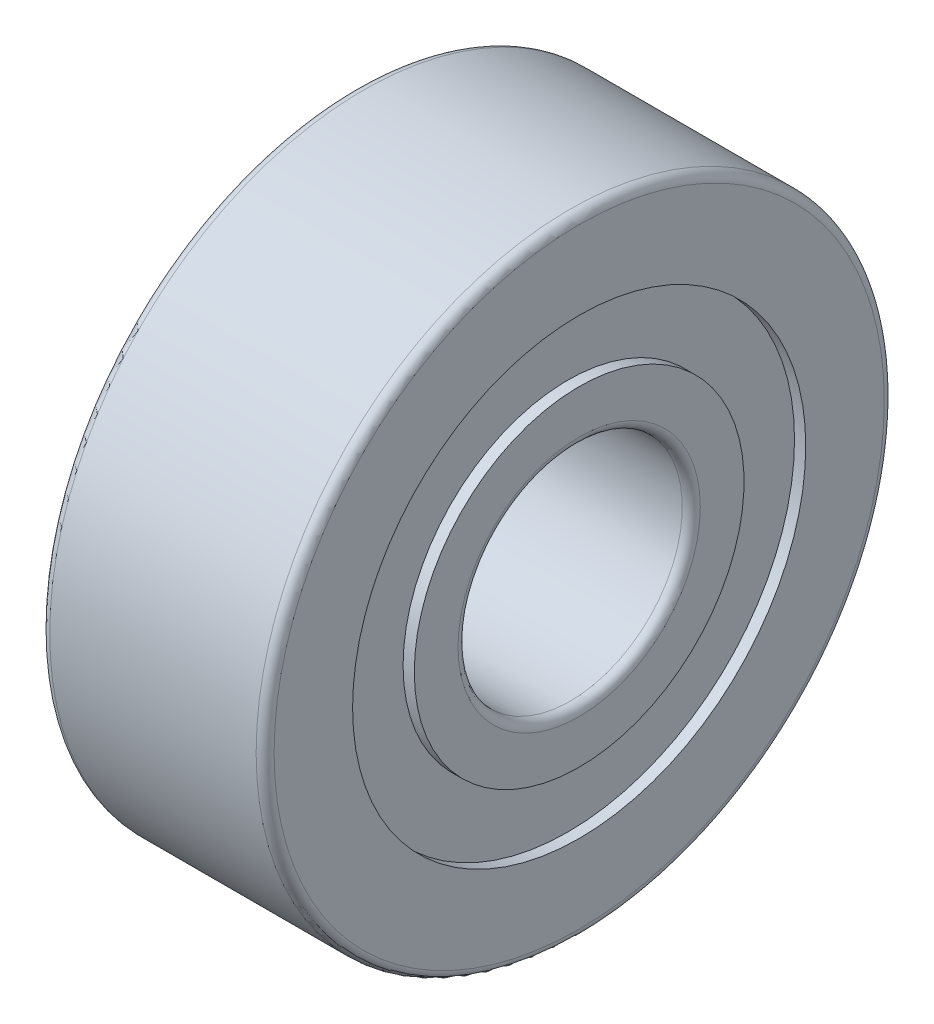
SolidWorks part; units mm, degrees
material "不锈钢 (铁素体)"
ref_plane "前视基准面" through (0, 0, 0) normal (0, 0, 1) x (1, 0, 0)
ref_plane "上视基准面" through (0, 0, 0) normal (0, 1, 0) x (1, 0, 0)
ref_plane "右视基准面" through (0, 0, 0) normal (1, 0, 0) x (0, 0, -1)
sketch "草图1" plane through (0, 0, 0) normal (0, 0, 1) x (1, 0, 0)
  line L0 (0, 0) -> (47.6548, 0) construction
  line L1 (0, 0) -> (0, 7) construction
  line L2 (-2.5, 7) -> (2.5, 7)
  line L3 (2.5, 7) -> (2.5, 5.05)
  line L4 (2.5, 5.05) -> (2.25, 5.05)
  line L5 (2.25, 5.05) -> (2.25, 3.675)
  line L6 (2.25, 3.675) -> (2.5, 3.675)
  line L7 (2.5, 3.675) -> (2.5, 2.5)
  line L8 (2.5, 2.5) -> (-2.5, 2.5)
  line L9 (-2.5, 3.675) -> (-2.5, 2.5)
  line L10 (-2.25, 3.675) -> (-2.5, 3.675)
  line L11 (-2.25, 5.05) -> (-2.25, 3.675)
  line L12 (-2.5, 5.05) -> (-2.25, 5.05)
  line L13 (-2.5, 7) -> (-2.5, 5.05)
  dimension "d_inner" = 5
  dimension "D_outer" = 14
  dimension "d2" = 7.35
  dimension "D3" = 10.1
  dimension "B" = 5
  dimension "D5" = 0.25
revolve "旋转1" add sketch "草图1" angle 360 about L0
fillet "圆角1" radius 0.2 4 edges at (-2.5, 0, 7) (2.5, 0, 7) (-2.5, 0, 2.5) (2.5, 0, 2.5)
equation "\"D5@草图1\" = 0.05 * \"B@草图1\""
